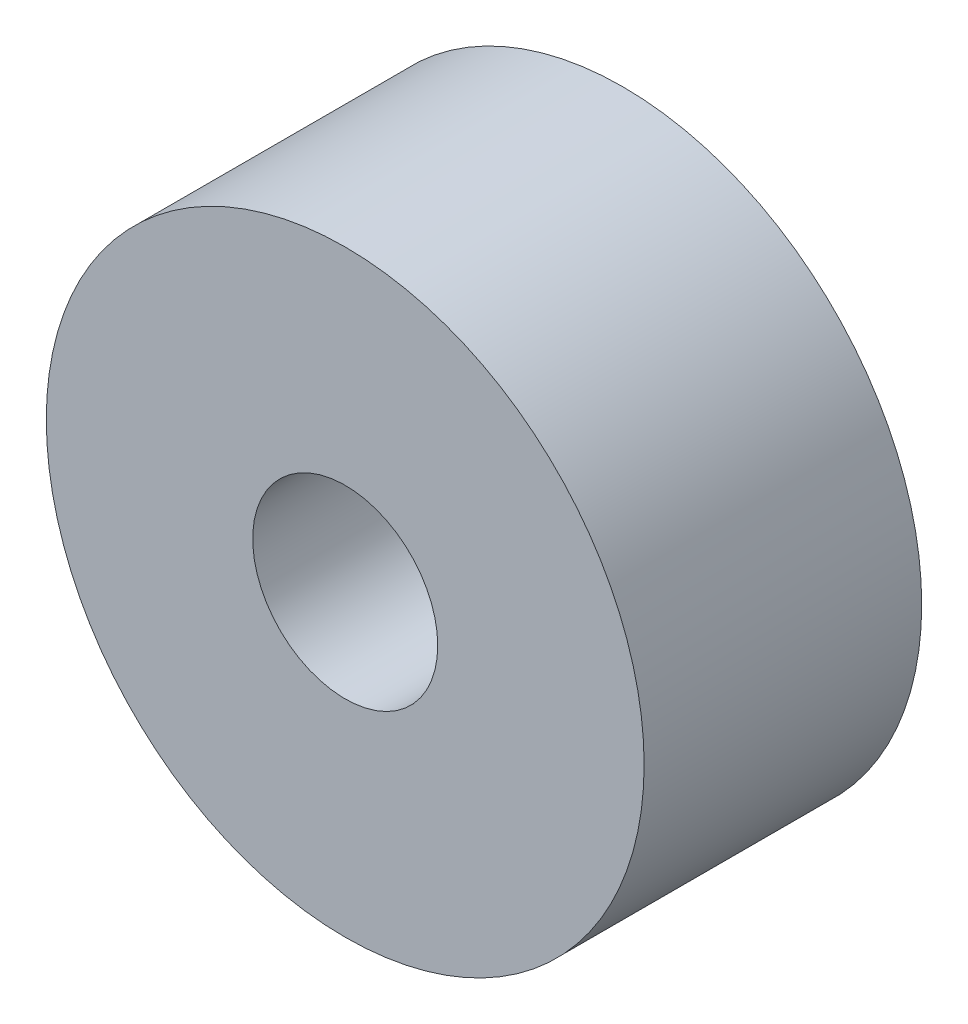
SolidWorks part; units mm, degrees
ref_plane "Спереди" through (0, 0, 0) normal (0, 0, 1) x (1, 0, 0)
ref_plane "Сверху" through (0, 0, 0) normal (0, 1, 0) x (1, 0, 0)
ref_plane "Справа" through (0, 0, 0) normal (1, 0, 0) x (0, 0, -1)
sketch "Эскиз1" plane through (0, 0, 0) normal (0, 0, 1) x (1, 0, 0)
  circle A0 centre (0, 0) radius 32.3077
  circle A1 centre (0, 0) radius 10
extrude "Carrier" add sketch "Эскиз1" along normal blind 30 from offset 15
